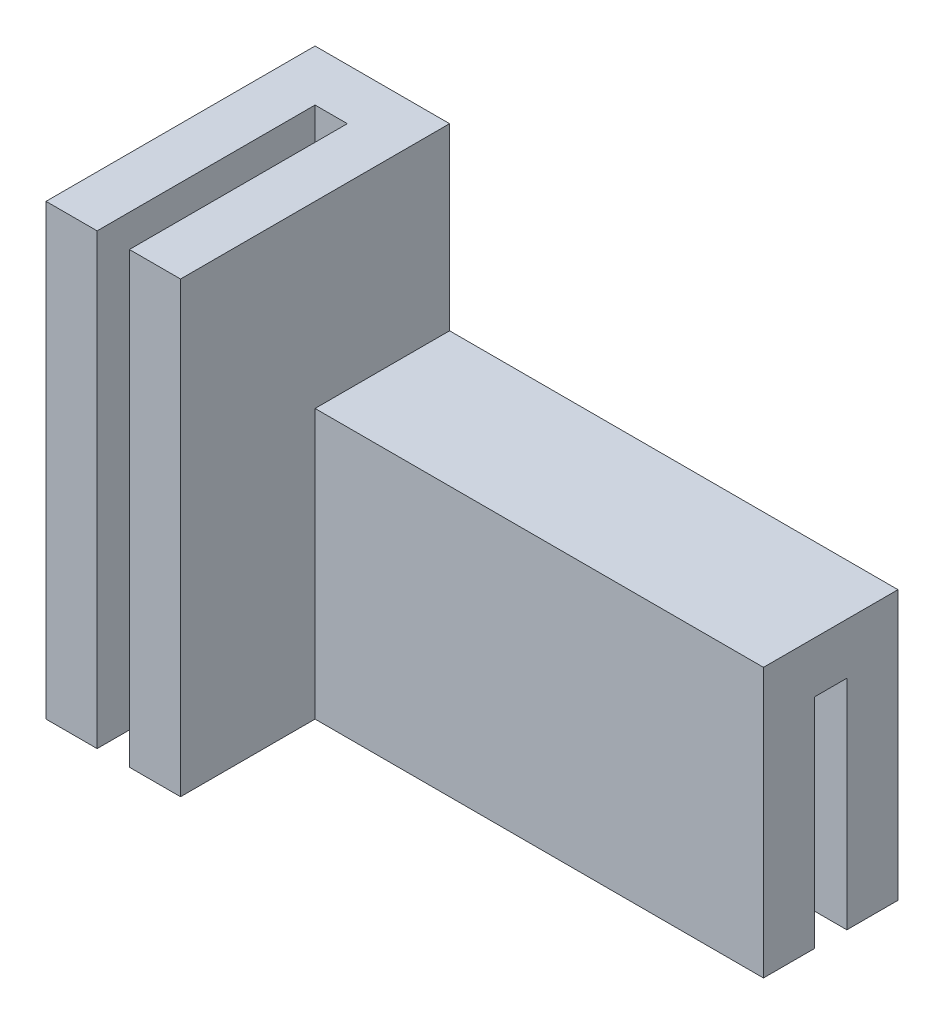
SolidWorks part; units mm, degrees
ref_plane "Plan de face" through (0, 0, 0) normal (0, 0, 1) x (1, 0, 0)
ref_plane "Plan de dessus" through (0, 0, 0) normal (0, 1, 0) x (1, 0, 0)
ref_plane "Plan de droite" through (0, 0, 0) normal (1, 0, 0) x (0, 0, -1)
sketch "Esquisse1" plane through (0, 0, 0) normal (0, 0, 1) x (1, 0, 0)
  line L1 (0, 0) -> (15, 0)
  line L2 (0, 0) -> (0, -50)
  line L3 (0, -50) -> (15, -50)
  line L4 (15, 0) -> (15, -50)
  dimension "D1" = 15
  dimension "D2" = 50
extrude "Boss.-Extru.1" add sketch "Esquisse1" along normal blind 30
sketch "Esquisse2" plane through (0, 0, 30) normal (0, 0, 1) x (1, 0, 0)
  line L0 (15, 0) -> (0, 0) construction
  line L1 (0, -50) -> (15, -50) construction
  line L2 (5.7, 0) -> (9.3, 0)
  line L3 (5.7, 0) -> (5.7, -50)
  line L4 (5.7, -50) -> (9.3, -50)
  line L5 (9.3, 0) -> (9.3, -50)
  point P0 (5.7, 0)
  point P1 (9.3, 0)
  dimension "D1" = 5.7
  dimension "D2" = 5.7
extrude "Enlèv. mat.-Extru.1" cut sketch "Esquisse2" against normal blind 24.3
sketch "Esquisse4" plane through (15, 0, 0) normal (1, 0, 0) x (0, 0, -1)
  line L0 (0, -50) -> (0, -20)
  line L1 (0, -50) -> (0, 0) construction
  line L2 (0, -20) -> (-15, -20)
  line L3 (-15, -20) -> (-15, -50)
  line L6 (-15, -50) -> (-9.3, -50)
  line L7 (-30, -50) -> (0, -50) construction
  line L8 (0, -50) -> (-5.7, -50)
  line L9 (-9.3, -50) -> (-9.3, -25.7)
  line L10 (-9.3, -25.7) -> (-5.7, -25.7)
  line L11 (-5.7, -25.7) -> (-5.7, -50)
  dimension "D1" = 30
  dimension "D2" = 15
  dimension "D3" = 5.7
  dimension "D4" = 5.7
  dimension "D5" = 24.3
extrude "Boss.-Extru.2" add sketch "Esquisse4" along normal blind 50
sketch "Esquisse5" plane through (15, 0, 0) normal (1, 0, 0) x (0, 0, -1)
  line L4 (-5.7, -50) -> (-5.7, -25.7)
  line L5 (-5.7, -25.7) -> (-9.3, -25.7)
  line L6 (-9.3, -25.7) -> (-9.3, -50)
  line L7 (-9.3, -50) -> (-5.7, -50)
  line L8 (-5.7, -50) -> (-5.7, -25.7)
  line L9 (-5.7, -25.7) -> (-9.3, -25.7)
  line L10 (-9.3, -25.7) -> (-9.3, -50)
  line L11 (-9.3, -50) -> (-5.7, -50)
  dimension "D1" = 0
extrude "Enlèv. mat.-Extru.2" cut sketch "Esquisse5" against normal blind 2
